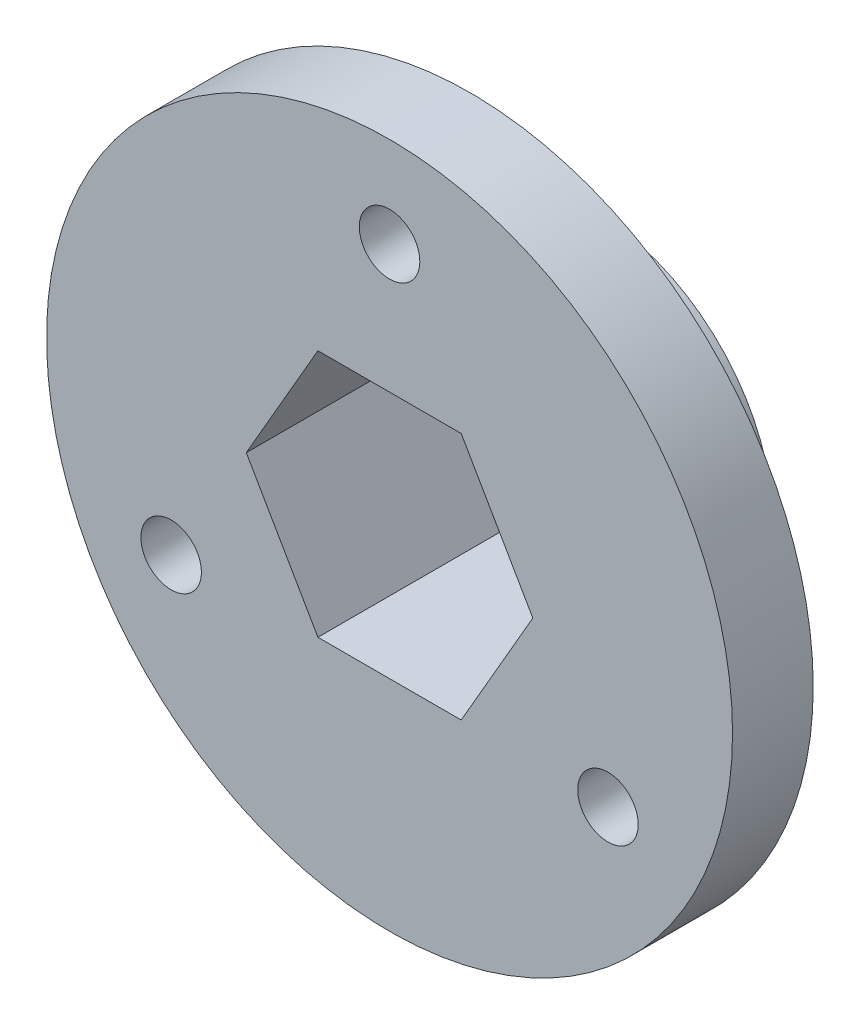
SolidWorks part; units mm, degrees
ref_plane "Alzado" through (0, 0, 0) normal (0, 0, 1) x (1, 0, 0)
ref_plane "Planta" through (0, 0, 0) normal (0, 1, 0) x (1, 0, 0)
ref_plane "Vista lateral" through (0, 0, 0) normal (1, 0, 0) x (0, 0, -1)
sketch "Croquis1" plane through (0, 0, 0) normal (0, 0, 1) x (1, 0, 0)
  line L0 (0, 15.6083) -> (0, -18.3127) construction
  line L1 (0, 0) -> (0, 12.5) construction
  circle A0 centre (0, 0) radius 17
  circle A1 centre (0, 0) radius 12.5 construction
  circle A2 centre (0, 12.5) radius 1.5
  circle A3 centre (10.8253, -6.25) radius 1.5
  circle A4 centre (-10.8253, -6.25) radius 1.5
  dimension "D1" = 34
  dimension "D2" = 3
  dimension "D3" = 25
  dimension "D4" = 3
extrude "Saliente-Extruir1" add sketch "Croquis1" along normal blind 4
sketch "Croquis2" plane through (0, 0, 0) normal (0, 0, -1) x (-1, 0, 0)
  line L1 (3.5507, 6.15) -> (-3.5507, 6.15)
  line L2 (-3.5507, 6.15) -> (-7.1014, 0)
  line L3 (-7.1014, 0) -> (-3.5507, -6.15)
  line L4 (-3.5507, -6.15) -> (3.5507, -6.15)
  line L5 (3.5507, -6.15) -> (7.1014, 0)
  line L6 (7.1014, 0) -> (3.5507, 6.15)
  circle A0 centre (0, 0) radius 6.15 construction
  dimension "D1" = 12.3
extrude "Cortar-Extruir1" cut sketch "Croquis2" against normal blind 4
sketch "Croquis3" plane through (0, 0, 0) normal (0, 0, -1) x (-1, 0, 0)
  line L0 (-7.1014, 0) -> (-3.5507, -6.15) construction
  line L1 (-3.5507, -6.15) -> (3.5507, -6.15) construction
  line L2 (3.5507, -6.15) -> (7.1014, 0) construction
  line L3 (7.1014, 0) -> (3.5507, 6.15) construction
  line L4 (3.5507, 6.15) -> (-3.5507, 6.15) construction
  line L5 (-3.5507, 6.15) -> (-7.1014, 0) construction
  line L6 (-7.1014, 0) -> (-3.5507, -6.15)
  line L7 (-3.5507, -6.15) -> (3.5507, -6.15)
  line L8 (3.5507, -6.15) -> (7.1014, 0)
  line L9 (7.1014, 0) -> (3.5507, 6.15)
  line L10 (3.5507, 6.15) -> (-3.5507, 6.15)
  line L11 (-3.5507, 6.15) -> (-7.1014, 0)
  circle A0 centre (0, 0) radius 9
  circle A1 centre (0, 0) radius 17
  circle A2 centre (0, 0) radius 17
  line M8 (-3.5507, 6.15) -> (3.5507, 6.15)
  line M9 (3.5507, 6.15) -> (7.1014, 0)
  line M10 (7.1014, 0) -> (3.5507, -6.15)
  line M11 (3.5507, -6.15) -> (-3.5507, -6.15)
  line M12 (-3.5507, -6.15) -> (-7.1014, 0)
  line M13 (-7.1014, 0) -> (-3.5507, 6.15)
  circle M15 centre (0, 12.5) radius 1.5
  circle M16 centre (-10.8253, -6.25) radius 1.5
  circle M17 centre (10.8253, -6.25) radius 1.5
  dimension "D2" = 18
  dimension "D1" = 0
extrude "Saliente-Extruir2" add sketch "Croquis3" along normal blind 6 contours A0 M15 M16 M17 M13 M8 M9 M10 M11 M12
